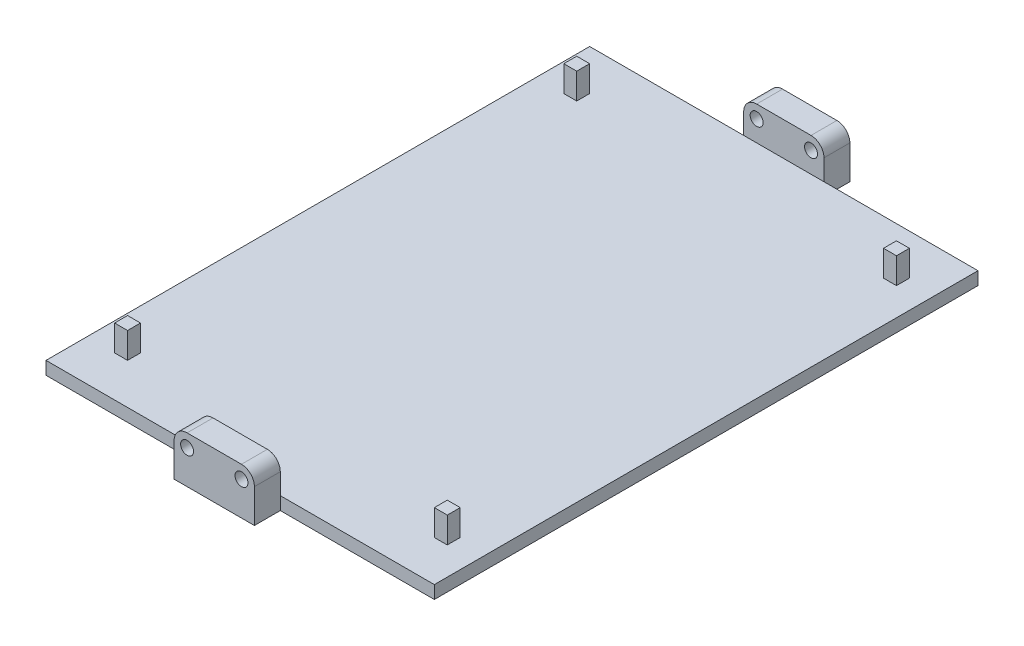
SolidWorks part; units mm, degrees
ref_plane "Front Plane" through (0, 0, 0) normal (0, 0, 1) x (1, 0, 0)
ref_plane "Top Plane" through (0, 0, 0) normal (0, 1, 0) x (1, 0, 0)
ref_plane "Right Plane" through (0, 0, 0) normal (1, 0, 0) x (0, 0, -1)
sketch "Sketch1" plane through (0, 0, 0) normal (0, 1, 0) x (1, 0, 0)
  line L1 (-30, 42) -> (30, 42)
  line L2 (-30, 42) -> (-30, -42)
  line L3 (-30, -42) -> (30, -42)
  line L4 (30, 42) -> (30, -42)
  line L5 (-30, 42) -> (30, -42) construction
  line L6 (-30, -42) -> (30, 42) construction
  point P0 (0, 0)
extrude "Boss-Extrude1" add sketch "Sketch1" along normal blind 2
sketch "Sketch2" plane through (0, 2, 0) normal (0, 1, 0) x (1, 0, 0)
  line L1 (-26, 36) -> (26, 36)
  line L2 (-26, 36) -> (-26, -36)
  line L3 (-26, -36) -> (26, -36)
  line L4 (26, 36) -> (26, -36)
  line L5 (-26, 36) -> (26, -36) construction
  line L6 (-26, -36) -> (26, 36) construction
  point P0 (0, 0)
sketch "Sketch4" plane through (0, 2, 0) normal (0, 1, 0) x (1, 0, 0)
  line L0 (-26, 36) -> (26, 36) construction
  line L1 (-25.7, 35.7) -> (-23.7, 35.7)
  line L2 (-25.7, 35.7) -> (-25.7, 33.7)
  line L3 (-25.7, 33.7) -> (-23.7, 33.7)
  line L4 (-23.7, 35.7) -> (-23.7, 33.7)
  line L5 (-25.7, 35.7) -> (-23.7, 33.7) construction
  line L6 (-25.7, 33.7) -> (-23.7, 35.7) construction
  line L7 (-26, 36) -> (-26, -36) construction
  line L8 (0, -1.1) -> (0, 1.1) construction
  line L9 (25.7, 33.7) -> (23.7, 33.7)
  line L10 (23.7, 35.7) -> (23.7, 33.7)
  line L11 (25.7, 35.7) -> (23.7, 35.7)
  line L12 (25.7, 35.7) -> (25.7, 33.7)
  line L13 (-1.1, 0) -> (1.1, 0) construction
  line L14 (25.7, -35.7) -> (25.7, -33.7)
  line L15 (25.7, -35.7) -> (23.7, -35.7)
  line L16 (23.7, -35.7) -> (23.7, -33.7)
  line L17 (25.7, -33.7) -> (23.7, -33.7)
  line L18 (-25.7, -33.7) -> (-23.7, -33.7)
  line L19 (-23.7, -35.7) -> (-23.7, -33.7)
  line L20 (-25.7, -35.7) -> (-23.7, -35.7)
  line L21 (-25.7, -35.7) -> (-25.7, -33.7)
  point P0 (-24.7, 34.7)
  dimension "D1" = 0.3
  dimension "D2" = 0.3
extrude "Boss-Extrude3" add sketch "Sketch4" along normal blind 4
sketch "Sketch5" plane through (0, 0, -42) normal (0, 0, -1) x (-1, 0, 0)
  line L0 (-30, 0) -> (30, 0) construction
  line L1 (0, 3.96) -> (0, -3.96) construction
  line L2 (-6.2, 5.2) -> (-6.2, 0)
  line L3 (-6.2, 0) -> (6.2, 0)
  line L4 (6.2, 0) -> (6.2, 5.2)
  line L5 (-4.2, 7.2) -> (4.2, 7.2)
  circle A0 centre (-4.2, 5.2) radius 1
  circle A1 centre (-4.2, 5.2) radius 2
  circle A2 centre (4.2, 5.2) radius 1
  circle A3 centre (4.2, 5.2) radius 2
  line M5 (-30, 0) -> (30, 0)
  line M7 (30, 2) -> (-30, 2)
  dimension "D1" = 5.2
  dimension "D2" = 4.2
extrude "Boss-Extrude4" add sketch "Sketch5" along normal blind 4 contours L4 L2 M5 M7 | L4 A3 L5 A1 L2 M7 | A1 A0 | A3 A2
mirror "Mirror1" about plane through (0, 0, 0) normal (0, 0, 1) of "Boss-Extrude4"
